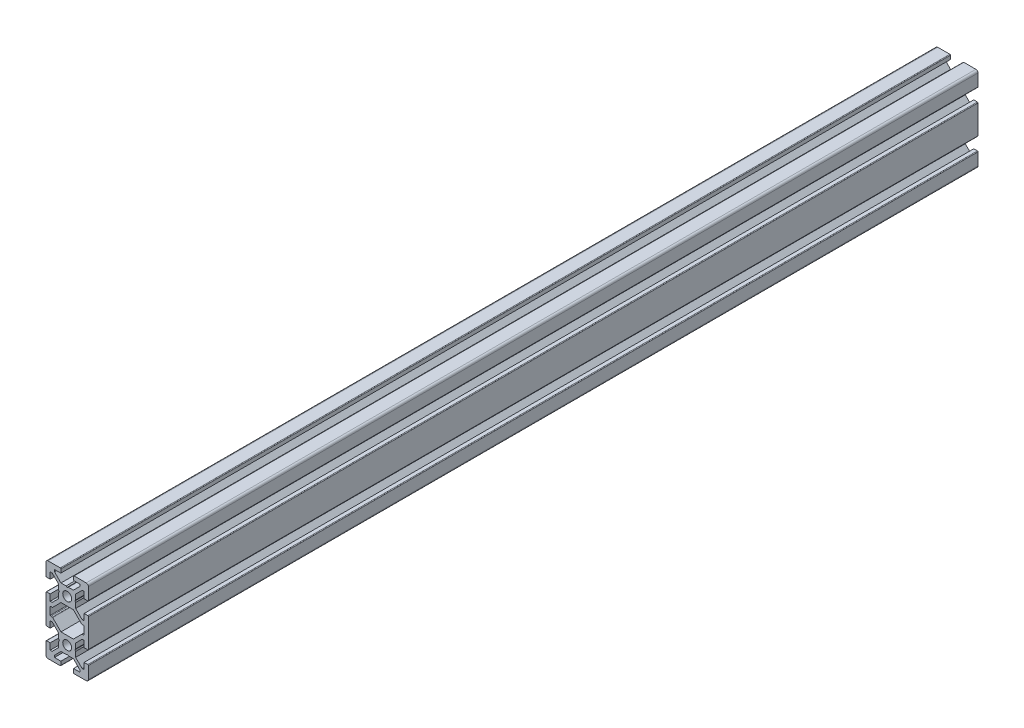
SolidWorks part; units mm, degrees
ref_plane "Front Plane" through (0, 0, 0) normal (0, 0, 1) x (1, 0, 0)
ref_plane "Top Plane" through (0, 0, 0) normal (0, 1, 0) x (1, 0, 0)
ref_plane "Right Plane" through (0, 0, 0) normal (1, 0, 0) x (0, 0, -1)
ref_plane "Plane1" through (0, 0, 0) normal (0, 0, 1) x (1, 0, 0)
sketch "Sketch1" plane through (0, 0, 0) normal (0, 0, 1) x (1, 0, 0)
  line L0 (-10, -13.3) -> (-10, -19)
  line L1 (-9, -20) -> (-3.3, -20)
  line L2 (-3, -19.7) -> (-3, -18)
  line L3 (-3, -18) -> (-6, -18)
  line L4 (-6, -18) -> (-6, -17.0607)
  line L5 (-6, -17.0607) -> (-2.9393, -14)
  line L6 (-2.9393, -14) -> (-0.5196, -14)
  line L7 (-0.5196, -14) -> (0, -13.7)
  line L8 (0, -13.7) -> (0.5196, -14)
  line L9 (0.5196, -14) -> (2.9393, -14)
  line L10 (2.9393, -14) -> (6, -17.0607)
  line L11 (6, -17.0607) -> (6, -18)
  line L12 (6, -18) -> (3, -18)
  line L13 (3, -18) -> (3, -19.7)
  line L14 (3.3, -20) -> (9, -20)
  line L15 (10, -19) -> (10, -13.3)
  line L16 (9.7, -13) -> (8, -13)
  line L17 (8, -13) -> (8, -16)
  line L18 (8, -16) -> (7.0607, -16)
  line L19 (7.0607, -16) -> (4, -12.9393)
  line L20 (4, -12.9393) -> (4, -10.5196)
  line L21 (4, -10.5196) -> (3.7, -10)
  line L22 (3.7, -10) -> (4, -9.4804)
  line L23 (4, -9.4804) -> (4, -7.0607)
  line L24 (4, -7.0607) -> (7.0607, -4)
  line L25 (7.0607, -4) -> (8, -4)
  line L26 (8, -4) -> (8, -7)
  line L27 (8, -7) -> (9.7, -7)
  line L28 (10, -6.7) -> (10, 6.7)
  line L29 (9.7, 7) -> (8, 7)
  line L30 (8, 7) -> (8, 4)
  line L31 (8, 4) -> (7.0607, 4)
  line L32 (7.0607, 4) -> (4, 7.0607)
  line L33 (4, 7.0607) -> (4, 9.4804)
  line L34 (4, 9.4804) -> (3.7, 10)
  line L35 (3.7, 10) -> (4, 10.5196)
  line L36 (4, 10.5196) -> (4, 12.9393)
  line L37 (4, 12.9393) -> (7.0607, 16)
  line L38 (7.0607, 16) -> (8, 16)
  line L39 (8, 16) -> (8, 13)
  line L40 (8, 13) -> (9.7, 13)
  line L41 (10, 13.3) -> (10, 19)
  line L42 (9, 20) -> (3.3, 20)
  line L43 (3, 19.7) -> (3, 18)
  line L44 (3, 18) -> (6, 18)
  line L45 (6, 18) -> (6, 17.0607)
  line L46 (6, 17.0607) -> (2.9394, 14)
  line L47 (2.9394, 14) -> (0.5196, 14)
  line L48 (0.5196, 14) -> (0, 13.7)
  line L49 (0, 13.7) -> (-0.5196, 14)
  line L50 (-0.5196, 14) -> (-2.9393, 14)
  line L51 (-2.9393, 14) -> (-6, 17.0607)
  line L52 (-6, 17.0607) -> (-6, 18)
  line L53 (-6, 18) -> (-3, 18)
  line L54 (-3, 18) -> (-3, 19.7)
  line L55 (-3.3, 20) -> (-9, 20)
  line L56 (-10, 19) -> (-10, 13.3)
  line L57 (-9.7, 13) -> (-8, 13)
  line L58 (-8, 13) -> (-8, 16)
  line L59 (-8, 16) -> (-7.0606, 16)
  line L60 (-7.0606, 16) -> (-4, 12.9394)
  line L61 (-4, 12.9394) -> (-4, 10.5196)
  line L62 (-4, 10.5196) -> (-3.7, 10)
  line L63 (-3.7, 10) -> (-4, 9.4804)
  line L64 (-4, 9.4804) -> (-4, 7.0607)
  line L65 (-4, 7.0607) -> (-7.0607, 4)
  line L66 (-7.0607, 4) -> (-8, 4)
  line L67 (-8, 4) -> (-8, 7)
  line L68 (-8, 7) -> (-9.7, 7)
  line L69 (-10, 6.7) -> (-10, -6.7)
  line L70 (-9.7, -7) -> (-8, -7)
  line L71 (-8, -7) -> (-8, -4)
  line L72 (-8, -4) -> (-7.0607, -4)
  line L73 (-7.0607, -4) -> (-4, -7.0607)
  line L74 (-4, -7.0607) -> (-4, -9.4804)
  line L75 (-4, -9.4804) -> (-3.7, -10)
  line L76 (-3.7, -10) -> (-4, -10.5196)
  line L77 (-4, -10.5196) -> (-4, -12.9394)
  line L78 (-4, -12.9394) -> (-7.0606, -16)
  line L79 (-7.0606, -16) -> (-8, -16)
  line L80 (-8, -16) -> (-8, -13)
  line L81 (-8, -13) -> (-9.7, -13)
  line L82 (-8, 1.7) -> (-8, -1.7)
  line L83 (-7.7, -2) -> (-7.0636, -2)
  line L84 (-6.8515, -2.0879) -> (-2.9393, -6)
  line L85 (-2.9393, -6) -> (2.9393, -6)
  line L86 (2.9393, -6) -> (6.8515, -2.0879)
  line L87 (7.0636, -2) -> (7.7, -2)
  line L88 (8, -1.7) -> (8, 1.7)
  line L89 (7.7, 2) -> (7.0636, 2)
  line L90 (6.8515, 2.0879) -> (2.9393, 6)
  line L91 (2.9393, 6) -> (-2.9393, 6)
  line L92 (-2.9393, 6) -> (-6.8515, 2.0879)
  line L93 (-7.0636, 2) -> (-7.7, 2)
  arc A0 (-10, -19) -> (-9, -20) centre (-9, -19) ccw
  arc A1 (-3.3, -20) -> (-3, -19.7) centre (-3.3, -19.7) ccw
  arc A2 (3, -19.7) -> (3.3, -20) centre (3.3, -19.7) ccw
  arc A3 (9, -20) -> (10, -19) centre (9, -19) ccw
  arc A4 (10, -13.3) -> (9.7, -13) centre (9.7, -13.3) ccw
  arc A5 (9.7, -7) -> (10, -6.7) centre (9.7, -6.7) ccw
  arc A6 (10, 6.7) -> (9.7, 7) centre (9.7, 6.7) ccw
  arc A7 (9.7, 13) -> (10, 13.3) centre (9.7, 13.3) ccw
  arc A8 (10, 19) -> (9, 20) centre (9, 19) ccw
  arc A9 (3.3, 20) -> (3, 19.7) centre (3.3, 19.7) ccw
  arc A10 (-3, 19.7) -> (-3.3, 20) centre (-3.3, 19.7) ccw
  arc A11 (-9, 20) -> (-10, 19) centre (-9, 19) ccw
  arc A12 (-10, 13.3) -> (-9.7, 13) centre (-9.7, 13.3) ccw
  arc A13 (-9.7, 7) -> (-10, 6.7) centre (-9.7, 6.7) ccw
  arc A14 (-10, -6.7) -> (-9.7, -7) centre (-9.7, -6.7) ccw
  arc A15 (-9.7, -13) -> (-10, -13.3) centre (-9.7, -13.3) ccw
  circle A16 centre (0, 10) radius 2.1
  circle A17 centre (0, -10) radius 2.1
  arc A18 (-8, -1.7) -> (-7.7, -2) centre (-7.7, -1.7) ccw
  arc A19 (-7.0636, -2) -> (-6.8515, -2.0879) centre (-7.0635, -2.2999) cw
  arc A20 (6.8515, -2.0879) -> (7.0636, -2) centre (7.0635, -2.2999) cw
  arc A21 (7.7, -2) -> (8, -1.7) centre (7.7, -1.7) ccw
  arc A22 (8, 1.7) -> (7.7, 2) centre (7.7, 1.7) ccw
  arc A23 (7.0636, 2) -> (6.8515, 2.0879) centre (7.0635, 2.2999) cw
  arc A24 (-6.8515, 2.0879) -> (-7.0636, 2) centre (-7.0635, 2.2998) cw
  arc A25 (-7.7, 2) -> (-8, 1.7) centre (-7.7, 1.7) ccw
  dimension "D6" = 4.2
  dimension "D1" = 40
  dimension "D2" = 20
  dimension "D3" = 6
  dimension "D4" = 7
  dimension "D5" = 14
  dimension "D7" = 4
  dimension "D8" = 6
  dimension "D9" = 2
  dimension "D10" = 12
  dimension "D11" = 16
extrude "Boss-Extrude1" add sketch "Sketch1" against normal blind 420
equation "\"D1@Boss-Extrude1\"=\"ExtrusionLength\""
